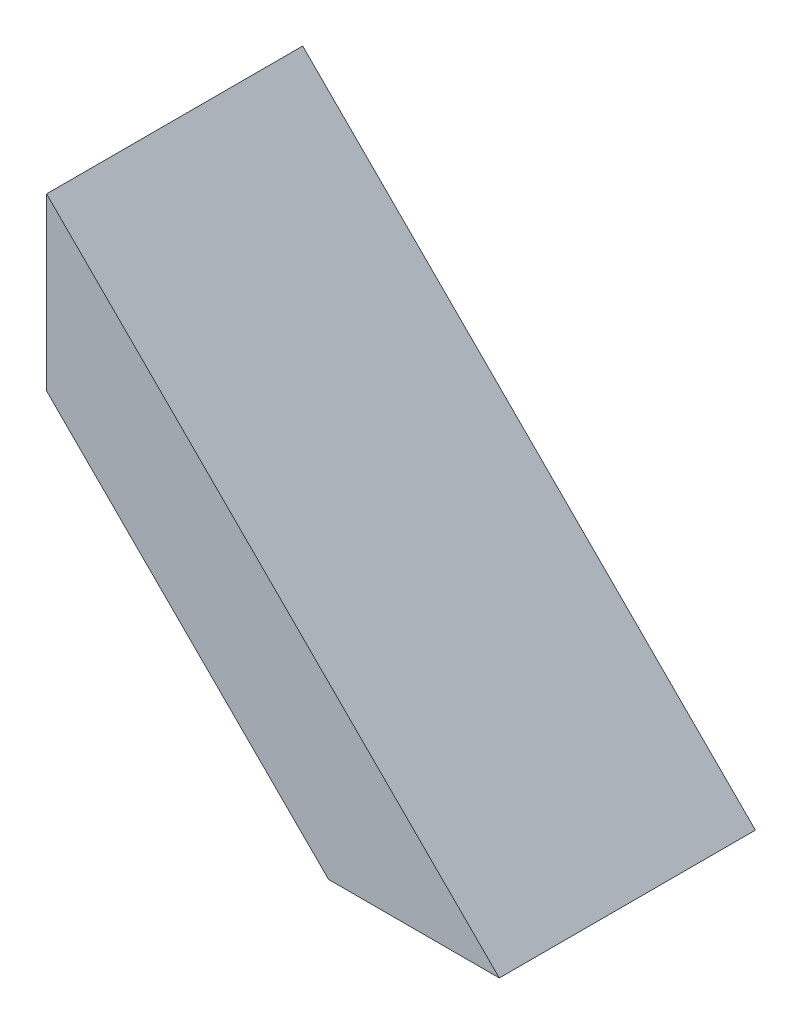
SolidWorks part; units mm, degrees
ref_plane "Front Plane" through (0, 0, 0) normal (0, 0, 1) x (1, 0, 0)
ref_plane "Top Plane" through (0, 0, 0) normal (0, 1, 0) x (1, 0, 0)
ref_plane "Right Plane" through (0, 0, 0) normal (1, 0, 0) x (0, 0, -1)
sketch "Sketch1" plane through (0, 0, 0) normal (0, 0, 1) x (1, 0, 0)
  line L0 (-7.1911, -0.2776) -> (-7.1911, -4.2776)
  line L1 (-7.1911, -4.2776) -> (-0.5845, -10.8842)
  line L2 (-0.5845, -10.8842) -> (3.4155, -10.8842)
  line L3 (3.4155, -10.8842) -> (-7.1911, -0.2776)
  dimension "D1" = 4
  dimension "D2" = 4
  dimension "D3" = 15
extrude "Boss-Extrude1" add sketch "Sketch1" along normal blind 6
